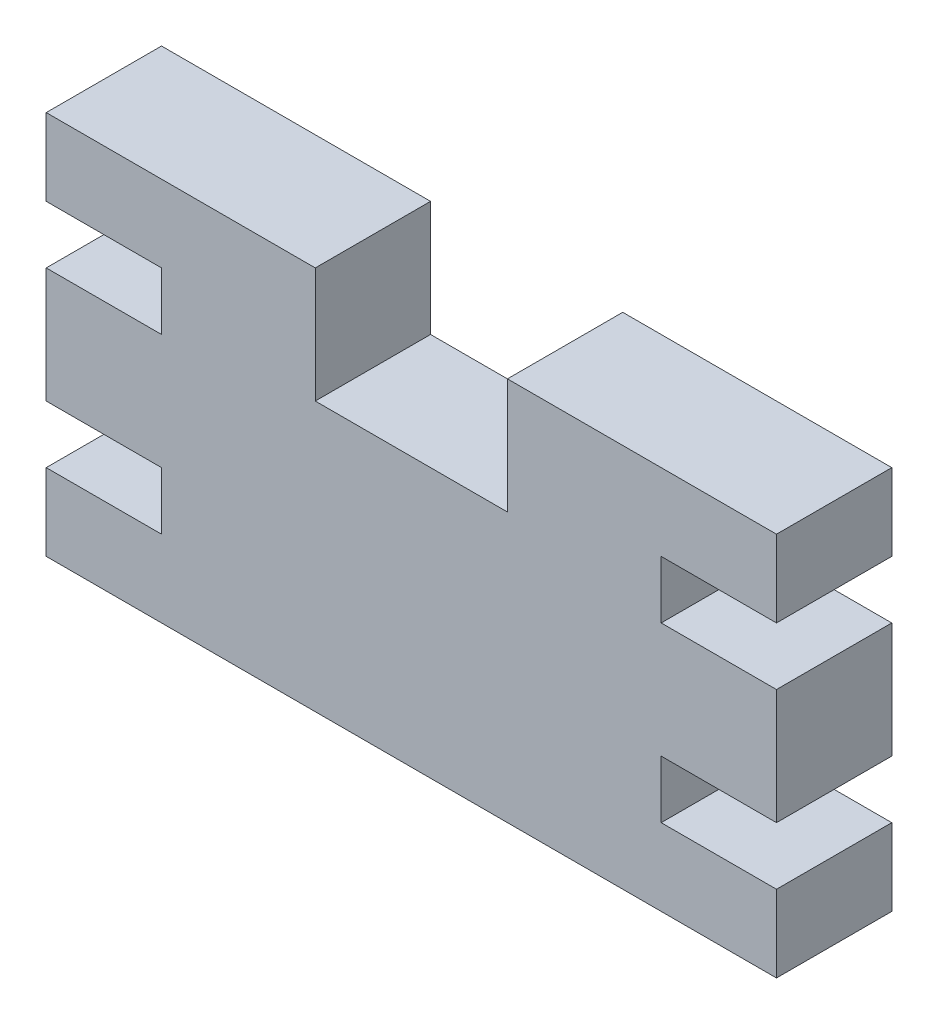
SolidWorks part; units mm, degrees
ref_plane "Plan de face" through (0, 0, 0) normal (0, 0, 1) x (1, 0, 0)
ref_plane "Plan de dessus" through (0, 0, 0) normal (0, 1, 0) x (1, 0, 0)
ref_plane "Plan de droite" through (0, 0, 0) normal (1, 0, 0) x (0, 0, -1)
sketch "Sketch1" plane through (0, 0, 0) normal (0, 0, 1) x (1, 0, 0)
  line L1 (12.5, 4.6335) -> (-6.5, 4.6335)
  line L2 (12.5, 4.6335) -> (12.5, 14.6335)
  line L3 (12.5, 14.6335) -> (-6.5, 14.6335)
  line L4 (-6.5, 4.6335) -> (-6.5, 14.6335)
  line L5 (12.5, 4.6335) -> (-6.5, 14.6335) construction
  line L6 (12.5, 14.6335) -> (-6.5, 4.6335) construction
  point P0 (3, 9.6335)
  dimension "D1" = 19
  dimension "D2" = 10
extrude "Boss-Extrude1" add sketch "Sketch1" along normal blind 3
sketch "Sketch2" plane through (0, 0, 3) normal (0, 0, 1) x (1, 0, 0)
  line L0 (-6.5, 14.6335) -> (-6.5, 4.6335) construction
  line L1 (-6.5, 12.6335) -> (-3.5, 12.6335)
  line L2 (-6.5, 12.6335) -> (-6.5, 11.1335)
  line L3 (-6.5, 11.1335) -> (-3.5, 11.1335)
  line L4 (-3.5, 12.6335) -> (-3.5, 11.1335)
  line L5 (12.5, 14.6335) -> (-6.5, 14.6335) construction
  line L7 (-6.5, 8.1335) -> (-3.5, 8.1335)
  line L8 (-6.5, 8.1335) -> (-6.5, 6.6335)
  line L9 (-6.5, 6.6335) -> (-3.5, 6.6335)
  line L10 (-3.5, 8.1335) -> (-3.5, 6.6335)
  dimension "D1" = 2
  dimension "D2" = 3
  dimension "D3" = 1.5
  dimension "D4" = 1.5
  dimension "D5" = 3
  dimension "D6" = 3
extrude "Cut-Extrude1" cut sketch "Sketch2" against normal blind 3
sketch "Sketch3" plane through (0, 0, 3) normal (0, 0, 1) x (1, 0, 0)
  line L0 (12.5, 4.6335) -> (12.5, 14.6335) construction
  line L1 (12.5, 12.6335) -> (9.5, 12.6335)
  line L2 (12.5, 12.6335) -> (12.5, 11.1335)
  line L3 (12.5, 11.1335) -> (9.5, 11.1335)
  line L4 (9.5, 12.6335) -> (9.5, 11.1335)
  line L5 (12.5, 14.6335) -> (-6.5, 14.6335) construction
  line L7 (12.5, 8.1335) -> (9.5, 8.1335)
  line L8 (12.5, 8.1335) -> (12.5, 6.6335)
  line L9 (12.5, 6.6335) -> (9.5, 6.6335)
  line L10 (9.5, 8.1335) -> (9.5, 6.6335)
  dimension "D1" = 3
  dimension "D2" = 1.5
  dimension "D3" = 2
  dimension "D4" = 3
  dimension "D5" = 1.5
  dimension "D6" = 3
extrude "Cut-Extrude2" cut sketch "Sketch3" against normal blind 3
sketch "Sketch5" plane through (0, 0, 3) normal (0, 0, 1) x (1, 0, 0)
  line L0 (12.5, 14.6335) -> (-6.5, 14.6335) construction
  line L1 (0.5, 14.6335) -> (5.5, 14.6335)
  line L2 (0.5, 14.6335) -> (0.5, 11.6335)
  line L3 (0.5, 11.6335) -> (5.5, 11.6335)
  line L4 (5.5, 14.6335) -> (5.5, 11.6335)
  line L5 (-6.5, 14.6335) -> (-6.5, 12.6335) construction
  dimension "D1" = 7
  dimension "D2" = 5
  dimension "D3" = 3
extrude "Cut-Extrude6" cut sketch "Sketch5" against normal blind 3
